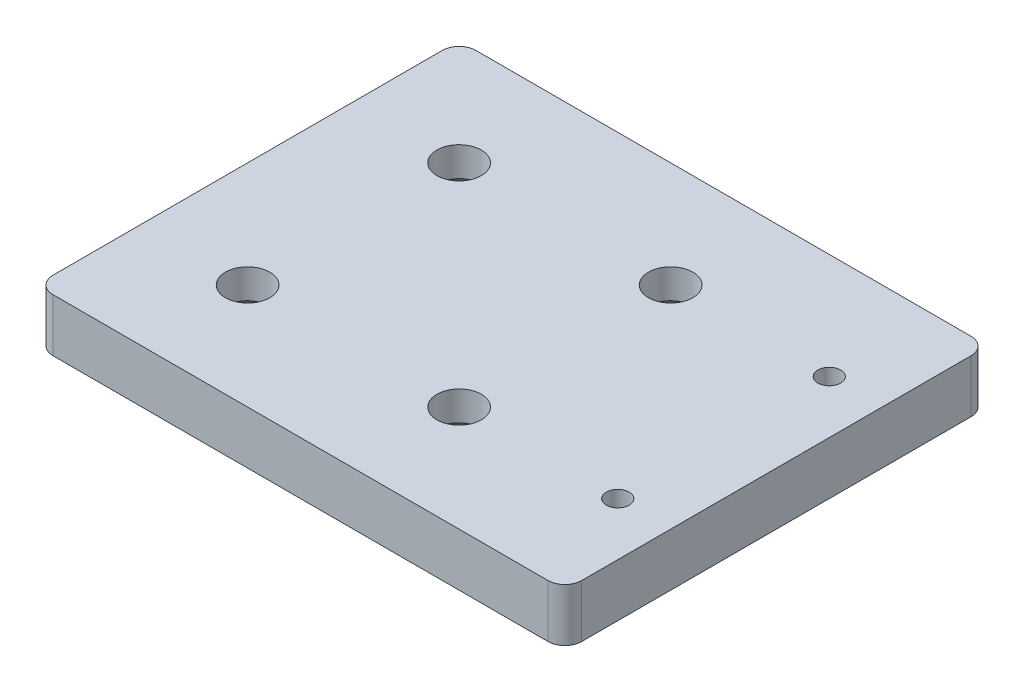
SolidWorks part; units mm, degrees
ref_plane "Front Plane" through (0, 0, 0) normal (0, 0, 1) x (1, 0, 0)
ref_plane "Top Plane" through (0, 0, 0) normal (0, 1, 0) x (1, 0, 0)
ref_plane "Right Plane" through (0, 0, 0) normal (1, 0, 0) x (0, 0, -1)
sketch "Sketch1" plane through (0, 0, 0) normal (0, 1, 0) x (1, 0, 0)
  line L1 (-46.82, -40) -> (46.82, -40)
  line L2 (-50, -36.82) -> (-50, 36.82)
  line L3 (-46.82, 40) -> (46.82, 40)
  line L4 (50, -36.82) -> (50, 36.82)
  line L5 (-50, -40) -> (50, 40) construction
  line L6 (-50, 40) -> (50, -40) construction
  arc A0 (-46.82, -40) -> (-50, -36.82) centre (-46.82, -36.82) cw
  arc A1 (46.82, -40) -> (50, -36.82) centre (46.82, -36.82) ccw
  arc A2 (46.82, 40) -> (50, 36.82) centre (46.82, 36.82) cw
  arc A3 (-50, 36.82) -> (-46.82, 40) centre (-46.82, 36.82) cw
  point P0 (0, 0)
  point P18 (-30, 20)
  point P22 (10, 20)
  point P23 (10, -20)
  point P24 (-30, -20)
  point P25 (40, 20)
  point P26 (40, -20)
  point P27 (10, -20)
  dimension "D3" = 3.18
  dimension "D1" = 100
  dimension "D2" = 80
  dimension "D4" = 20
  dimension "D5" = 20
  dimension "D10" = 10
  dimension "D11" = 40
  dimension "D12" = 20
  dimension "D6" = 2
  dimension "D7" = 2
  dimension "D8" = 2
  dimension "D9" = 2
extrude "Boss-Extrude1" add sketch "Sketch1" along normal blind 10 contours L2 A3 L3 A2 L4 A1 L1 A0
hole_wizard "CSK for M8 Flat Head Machine Screw1" positions "Sketch4" profile "Sketch5" countersink size "M8" standard "ANSI Metric" end condition through all
sketch "Sketch4" plane through (0, 0, 0) normal (0, -1, 0) x (-1, 0, 0)
  point P0 (-10, 20)
  point P3 (30, 20)
  point P6 (30, -20)
  point P9 (-10, -20)
sketch "Sketch5" plane through (10, 0, -20) normal (1, 0, 0) x (0, 0, -1)
  line L0 (0, 0) -> (0, 10)
  line L1 (0, 10) -> (4.2, 10)
  line L2 (4.2, 10) -> (4.2, 4.45)
  line L3 (4.2, 4.45) -> (8.65, 0)
  line L5 (8.65, 0) -> (0, 0)
  line L6 (-4.2, 4.45) -> (-8.65, 0) construction
  line L11 (0, -6.35) -> (0, 107.95) construction
  dimension "Thru Hole Dia." = 8.4
  dimension "Thru Hole Depth" = 10
  dimension "Near C'Sink Dia." = 17.3
  dimension "Near C'Sink Angle" = 90
hole_wizard "M4 Clearance Hole1" positions "Sketch6" profile "Sketch7" hole size "M4" standard "ANSI Metric" end condition through all
sketch "Sketch6" plane through (0, 0, 0) normal (0, -1, 0) x (-1, 0, 0)
  point P0 (-40, 20)
  point P3 (-40, -20)
sketch "Sketch7" plane through (40, 0, -20) normal (1, 0, 0) x (0, 0, -1)
  line L0 (0, 0) -> (0, 10)
  line L1 (0, 10) -> (2.15, 10)
  line L2 (2.15, 10) -> (2.15, 0)
  line L5 (2.15, 0) -> (0, 0)
  line L11 (0, -6.35) -> (0, 107.95) construction
  dimension "Thru Hole Dia." = 4.3
  dimension "Thru Hole Depth" = 10
